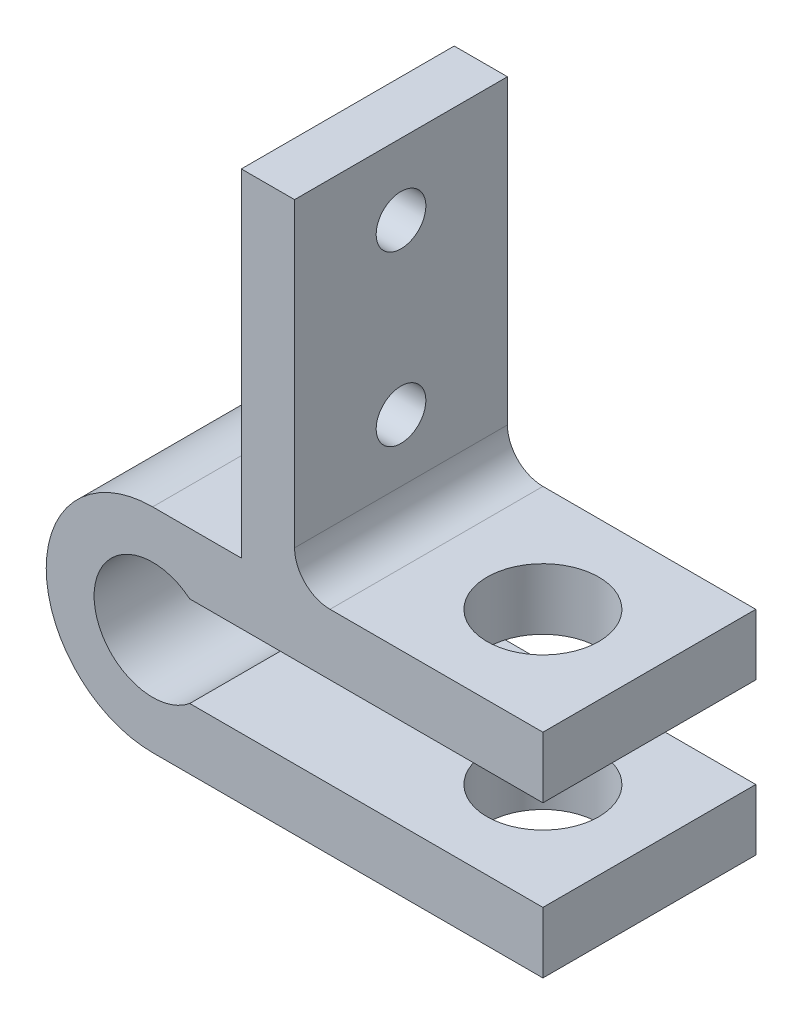
SolidWorks part; units mm, degrees
ref_plane "Front Plane" through (0, 0, 0) normal (0, 0, 1) x (1, 0, 0)
ref_plane "Top Plane" through (0, 0, 0) normal (0, 1, 0) x (1, 0, 0)
ref_plane "Right Plane" through (0, 0, 0) normal (1, 0, 0) x (0, 0, -1)
sketch "Sketch1" plane through (0, 0, 0) normal (0, 0, 1) x (1, 0, 0)
  line L0 (10, 6) -> (22, 6)
  line L1 (22, 6) -> (22, 2.5527)
  line L2 (22, 2.5527) -> (2.0913, 2.5527)
  line L3 (-11.5353, 0) -> (18.1518, 0) construction
  line L4 (22, -2.5527) -> (2.0913, -2.5527)
  line L5 (22, -6) -> (22, -2.5527)
  line L6 (0, -6) -> (22, -6)
  line L7 (5, 6) -> (5, 25)
  line L8 (5, 25) -> (8, 25)
  line L9 (8, 25) -> (8, 8)
  line L10 (0, 6) -> (5, 6)
  arc A0 (2.0913, 2.5527) -> (2.0913, -2.5527) centre (0, 0) ccw
  arc A1 (8, 8) -> (10, 6) centre (10, 8) ccw
  arc A2 (0, 6) -> (0, -6) centre (0, 0) ccw
  dimension "D1" = 3.3
  dimension "D2" = 6
  dimension "D5" = 2
  dimension "D3" = 22
  dimension "D4" = 5.1054
  dimension "D6" = 3
  dimension "D7" = 25
  dimension "D8" = 5
extrude "Boss-Extrude1" add sketch "Sketch1" along normal blind 12
sketch "Sketch2" plane through (0, 0, 0) normal (0, 1, 0) x (1, 0, 0)
  line L1 (16, -6) -> (5, -6) construction
  line L2 (5, -12) -> (5, 0) construction
  circle A0 centre (16, -6) radius 3.15
  dimension "D3" = 6.3
  dimension "D1" = 16
extrude "Cut-Extrude1" cut sketch "Sketch2" against normal through all and the other way through all
sketch "Sketch3" plane through (5, 0, 0) normal (-1, 0, 0) x (0, 0, 1)
  line L0 (6, 25) -> (6, -3.3166) construction
  line L1 (12, 25) -> (0, 25) construction
  line L2 (12, -3.3166) -> (0, -3.3166) construction
  circle A0 centre (6, 21) radius 1.4
  circle A1 centre (6, 11.5) radius 1.4
  dimension "D2" = 2.8
  dimension "D1" = 9.5
  dimension "D3" = 4
extrude "Cut-Extrude2" cut sketch "Sketch3" against normal up to next
